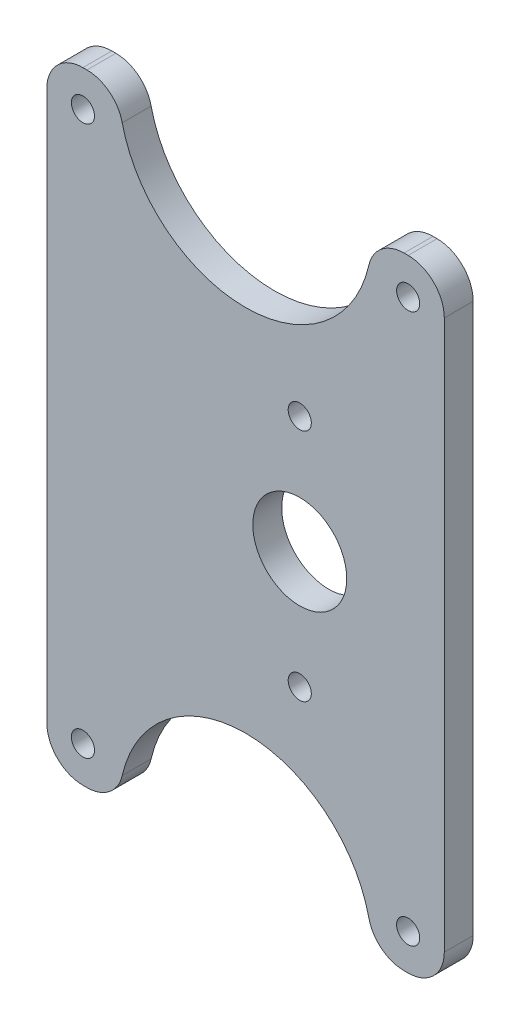
SolidWorks part; units mm, degrees
material "5052-O"
ref_plane "正面" through (0, 0, 0) normal (0, 0, 1) x (1, 0, 0)
ref_plane "平面" through (0, 0, 0) normal (0, 1, 0) x (1, 0, 0)
ref_plane "右側面" through (0, 0, 0) normal (1, 0, 0) x (0, 0, -1)
sketch "ｽｹｯﾁ1" plane through (0, 0, 0) normal (0, 0, 1) x (1, 0, 0)
  line L1 (-27.5, 43) -> (27.5, 43)
  line L2 (-27.5, 43) -> (-27.5, -43)
  line L3 (-27.5, -43) -> (27.5, -43)
  line L4 (27.5, 43) -> (27.5, -43)
  line L5 (-27.5, 43) -> (27.5, -43) construction
  line L6 (-27.5, -43) -> (27.5, 43) construction
  point P0 (0, 0)
  dimension "D1" = 55
  dimension "D2" = 86
extrude "ﾎﾞｽ - 押し出し1" add sketch "ｽｹｯﾁ1" along normal mid plane 4
sketch "ｽｹｯﾁ2" plane through (0, 0, 2) normal (0, 0, 1) x (1, 0, 0)
  line L0 (-27.5, 43) -> (-27.5, -43) construction
  circle A10 centre (7.5, 0) radius 6.5
  dimension "D2" = 35
  dimension "D10" = 13
extrude "ｶｯﾄ - 押し出し1" cut sketch "ｽｹｯﾁ2" against normal through all
sketch "ｽｹｯﾁ3" plane through (0, 0, 2) normal (0, 0, 1) x (1, 0, 0)
  line L0 (27.5, 43) -> (-27.5, 43) construction
  line L1 (-27.5, 43) -> (-27.5, -43) construction
  line L2 (0, -2.2) -> (0, 2.2) construction
  line L3 (2.2, 0) -> (-2.2, 0) construction
  circle A0 centre (-22.5, 38) radius 1.6
  circle A1 centre (22.5, 38) radius 1.6
  circle A2 centre (22.5, -38) radius 1.6
  circle A3 centre (-22.5, -38) radius 1.6
  dimension "D1" = 3.2
  dimension "D2" = 5
  dimension "D3" = 5
extrude "ｶｯﾄ - 押し出し2" cut sketch "ｽｹｯﾁ3" against normal through all
sketch "ｽｹｯﾁ4" plane through (0, 0, -2) normal (0, 0, -1) x (-1, 0, 0)
  circle A0 centre (-7.5, 16.215) radius 1.6
  circle A1 centre (-7.5, -16.215) radius 1.6
  dimension "D1" = 3.2
  dimension "D2" = 3.2
extrude "ｶｯﾄ - 押し出し3" cut sketch "ｽｹｯﾁ4" against normal through all
sketch "ｽｹｯﾁ7" plane through (0, 0, 2) normal (0, 0, 1) x (1, 0, 0)
  line L0 (27.5, 43) -> (-27.5, 43) construction
  line L1 (2.2, 0) -> (-2.2, 0) construction
  circle A0 centre (0, 43) radius 17.5
  circle A1 centre (0, -43) radius 17.5
  dimension "D2" = 35
  dimension "D1" = 0
extrude "ｶｯﾄ - 押し出し6" cut sketch "ｽｹｯﾁ7" against normal through all
fillet "ﾌｨﾚｯﾄ2" radius 5 8 edges at (-27.5, 43, 0) (-27.5, -43, 0) (27.5, -43, 0) (27.5, 43, 0) (17.5, -43, 0) (-17.5, -43, 0) (-17.5, 43, 0) (17.5, 43, 0)
